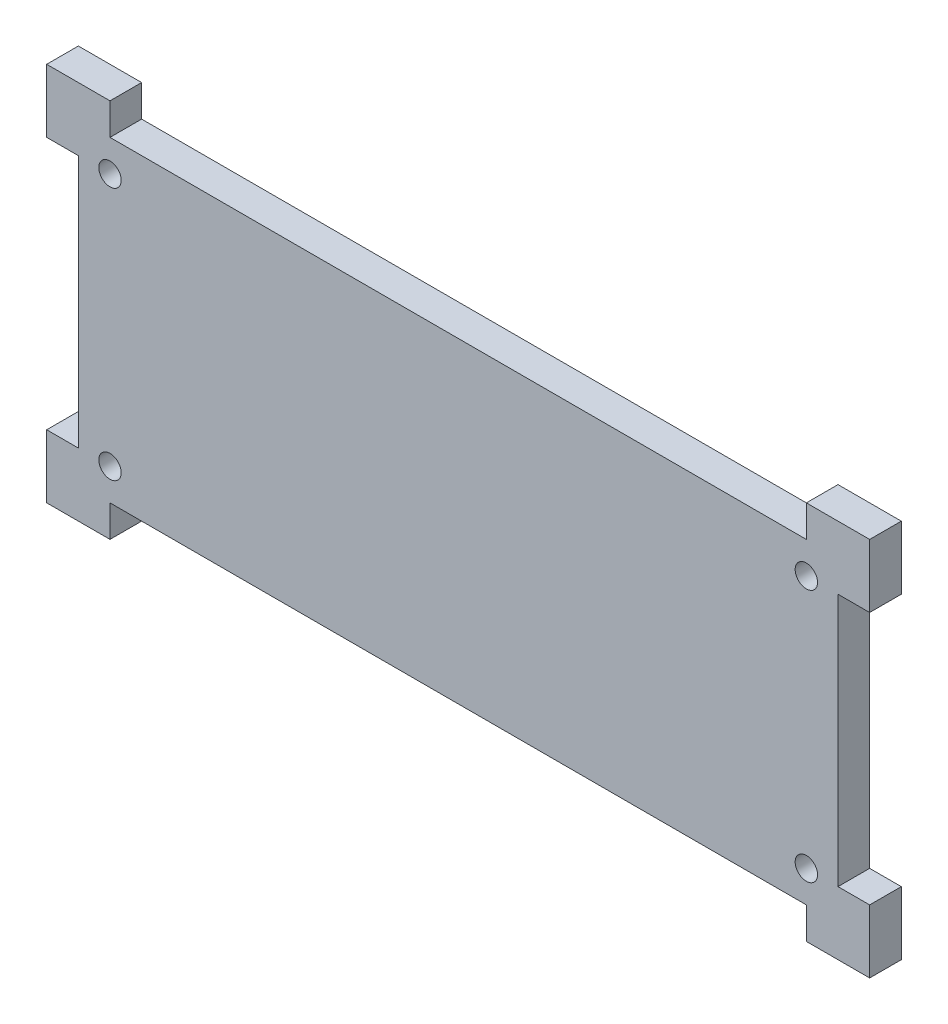
SolidWorks part; units mm, degrees
ref_plane "Front Plane" through (0, 0, 0) normal (0, 0, 1) x (1, 0, 0)
ref_plane "Top Plane" through (0, 0, 0) normal (0, 1, 0) x (1, 0, 0)
ref_plane "Right Plane" through (0, 0, 0) normal (1, 0, 0) x (0, 0, -1)
sketch "Sketch1" plane through (0, 0, 0) normal (0, 0, 1) x (1, 0, 0)
  line L0 (-107.95, -6.35) -> (-107.95, 6.35)
  line L1 (-107.95, 6.35) -> (-101.6, 6.35)
  line L2 (-101.6, 6.35) -> (-101.6, 57.15)
  line L3 (-101.6, 57.15) -> (-107.95, 57.15)
  line L4 (-107.95, 57.15) -> (-107.95, 69.85)
  line L5 (-107.95, 69.85) -> (-95.25, 69.85)
  line L6 (-95.25, 69.85) -> (-95.25, 63.5)
  line L7 (-95.25, 63.5) -> (44.45, 63.5)
  line L8 (44.45, 63.5) -> (44.45, 69.85)
  line L9 (44.45, 69.85) -> (57.15, 69.85)
  line L10 (101.6, 69.85) -> (44.45, 69.85) construction
  line L11 (57.15, 69.85) -> (57.15, 57.15)
  line L12 (57.15, 57.15) -> (50.8, 57.15)
  line L13 (50.8, 57.15) -> (50.8, 6.35)
  line L14 (50.8, 6.35) -> (57.15, 6.35)
  line L15 (57.15, 6.35) -> (57.15, -6.35)
  line L16 (57.15, -6.35) -> (44.45, -6.35)
  line L17 (44.45, -6.35) -> (44.45, 0)
  line L18 (44.45, 0) -> (-95.25, 0)
  line L19 (-95.25, 0) -> (-95.25, -6.35)
  line L20 (-95.25, -6.35) -> (-107.95, -6.35)
extrude "Boss-Extrude1" add sketch "Sketch1" along normal up to surface (6.35 mm away)
sketch "Sketch2" plane through (0, 0, 6.35) normal (0, 0, 1) x (1, 0, 0)
  circle A0 centre (44.45, 6.35) radius 2.2479
  circle A1 centre (44.45, 57.15) radius 2.2479
  circle A2 centre (-95.25, 57.15) radius 2.2479
  circle A3 centre (-95.25, 6.35) radius 2.2479
  dimension "D1" = 4.4958
extrude "Cut-Extrude4" cut sketch "Sketch2" against normal through all
